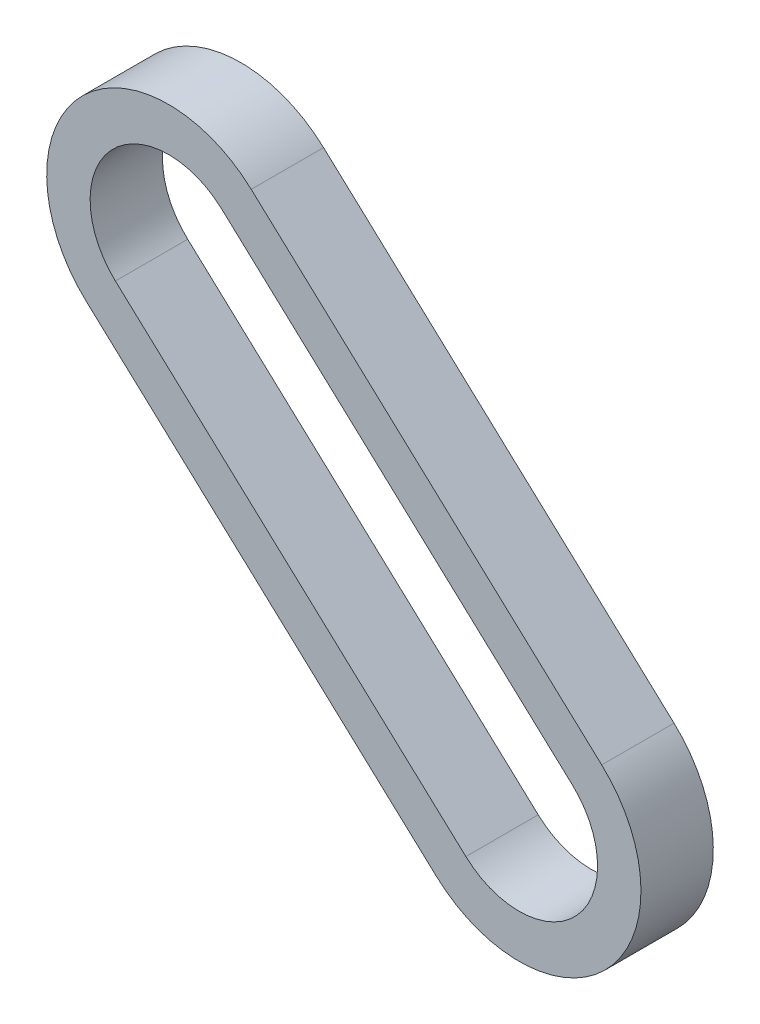
SolidWorks part; units mm, degrees
ref_plane "Front Plane" through (0, 0, 0) normal (0, 0, 1) x (1, 0, 0)
ref_plane "Top Plane" through (0, 0, 0) normal (0, 1, 0) x (1, 0, 0)
ref_plane "Right Plane" through (0, 0, 0) normal (1, 0, 0) x (0, 0, -1)
sketch "Sketch2" plane through (0, 0, 0) normal (0, 0, 1) x (1, 0, 0)
  line L0 (0, 0) -> (1, 0) construction
  line L1 (0, 0) -> (0, 1) construction
  line L2 (0.1322, -14.9231) -> (-48.3237, 29.7607)
  line L3 (-33.613, 45.7133) -> (14.8429, 1.0295)
  arc A0 (14.8429, 1.0295) -> (0.1322, -14.9231) centre (7.4875, -6.9468) cw
  arc A1 (-48.3237, 29.7607) -> (-33.613, 45.7133) centre (-40.9684, 37.737) cw
extrude "Extrude-Thin1" add sketch "Sketch2" along normal blind 10 thin thin type one direction wall 6
